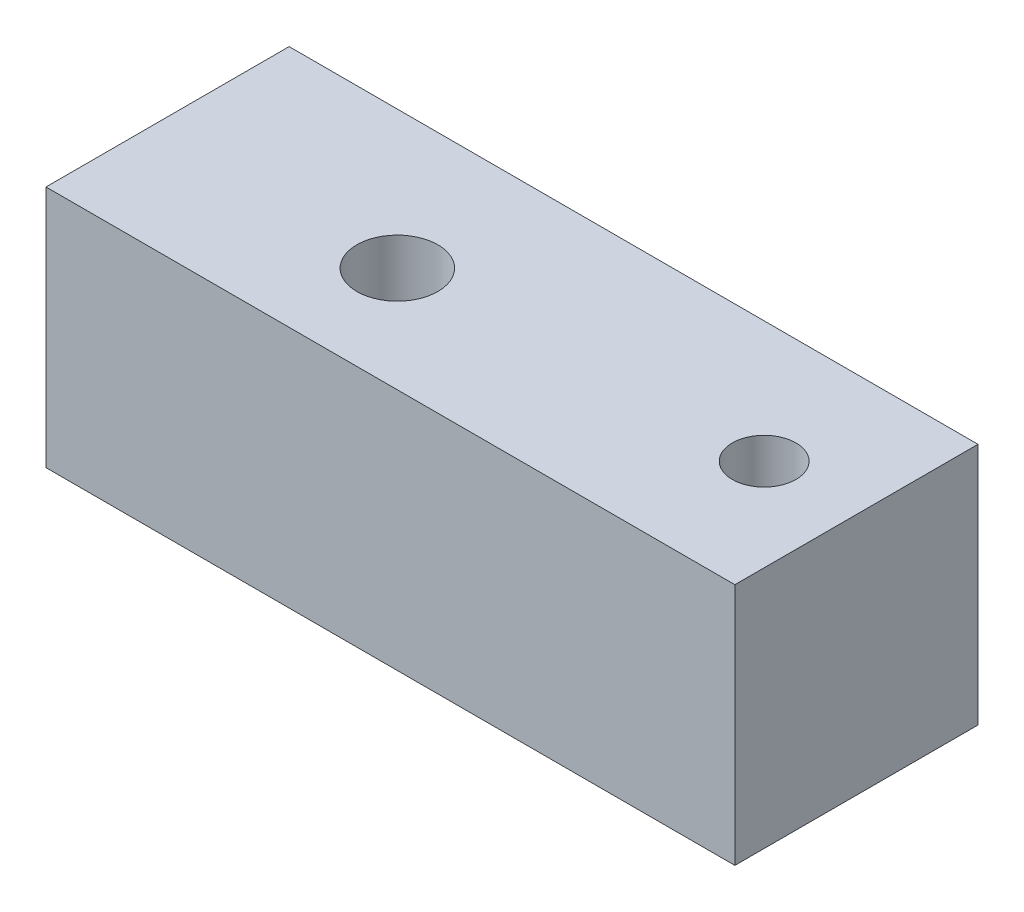
SolidWorks part; units mm, degrees
ref_plane "Front Plane" through (0, 0, 0) normal (0, 0, 1) x (1, 0, 0)
ref_plane "Top Plane" through (0, 0, 0) normal (0, 1, 0) x (1, 0, 0)
ref_plane "Right Plane" through (0, 0, 0) normal (1, 0, 0) x (0, 0, -1)
sketch "Sketch2" plane through (0, 0, 0) normal (0, 0, 1) x (1, 0, 0)
  line L1 (237.8344, -12.7) -> (183.8594, -12.7)
  line L2 (320.675, -12.7) -> (-320.675, -12.7) construction
  line L3 (237.8344, -12.7) -> (237.8344, 6.35)
  line L5 (237.8344, 6.35) -> (183.8594, 6.35)
  line L6 (183.8594, 6.35) -> (183.8594, -12.7)
  dimension "D1" = 53.975
extrude "Boss-Extrude1" add sketch "Sketch2" along normal blind 19.05
sketch "Sketch4" plane through (0, 6.35, 0) normal (0, 1, 0) x (1, 0, 0)
  point P0 (203.1334, -10.795)
hole_wizard "1/4 (0.25) Diameter Hole1" positions "Sketch7" profile "Sketch8" hole size "1/4" standard "ANSI Inch" end condition through all
sketch "Sketch7" plane through (0, 6.35, 0) normal (0, 1, 0) x (1, 0, 0)
  point P0 (203.1334, -10.795)
sketch "Sketch8" plane through (203.1334, 6.35, 10.795) normal (1, 0, 0) x (0, 0, 1)
  line L0 (0, 0) -> (0, 19.05)
  line L1 (0, 19.05) -> (3.175, 19.05)
  line L2 (3.175, 19.05) -> (3.175, 0)
  line L5 (3.175, 0) -> (0, 0)
  line L11 (0, -6.35) -> (0, 107.95) construction
  dimension "Thru Hole Dia." = 6.35
  dimension "Thru Hole Depth" = 19.05
hole_wizard "#10 Clearance Hole1" positions "Sketch9" profile "Sketch10" hole size "#10" standard "ANSI Inch" end condition through all
sketch "Sketch9" plane through (0, 6.35, 0) normal (0, 1, 0) x (1, 0, 0)
  point P0 (230.6024, -9.525)
sketch "Sketch10" plane through (230.6024, 6.35, 9.525) normal (1, 0, 0) x (0, 0, 1)
  line L0 (0, 0) -> (0, 19.05)
  line L1 (0, 19.05) -> (5.2197, 19.05)
  line L2 (2.4892, 15.9089) -> (2.4892, 0)
  line L5 (2.4892, 0) -> (0, 0)
  line L7 (5.2197, 19.05) -> (2.4892, 15.9089)
  line L8 (-5.2197, 19.05) -> (-2.4892, 15.9089) construction
  line L11 (0, -6.35) -> (0, 107.95) construction
  dimension "Thru Hole Dia." = 4.9784
  dimension "Thru Hole Depth" = 19.05
  dimension "Far C'Sink Dia." = 10.4394
  dimension "Far C'Sink Angle" = 82
